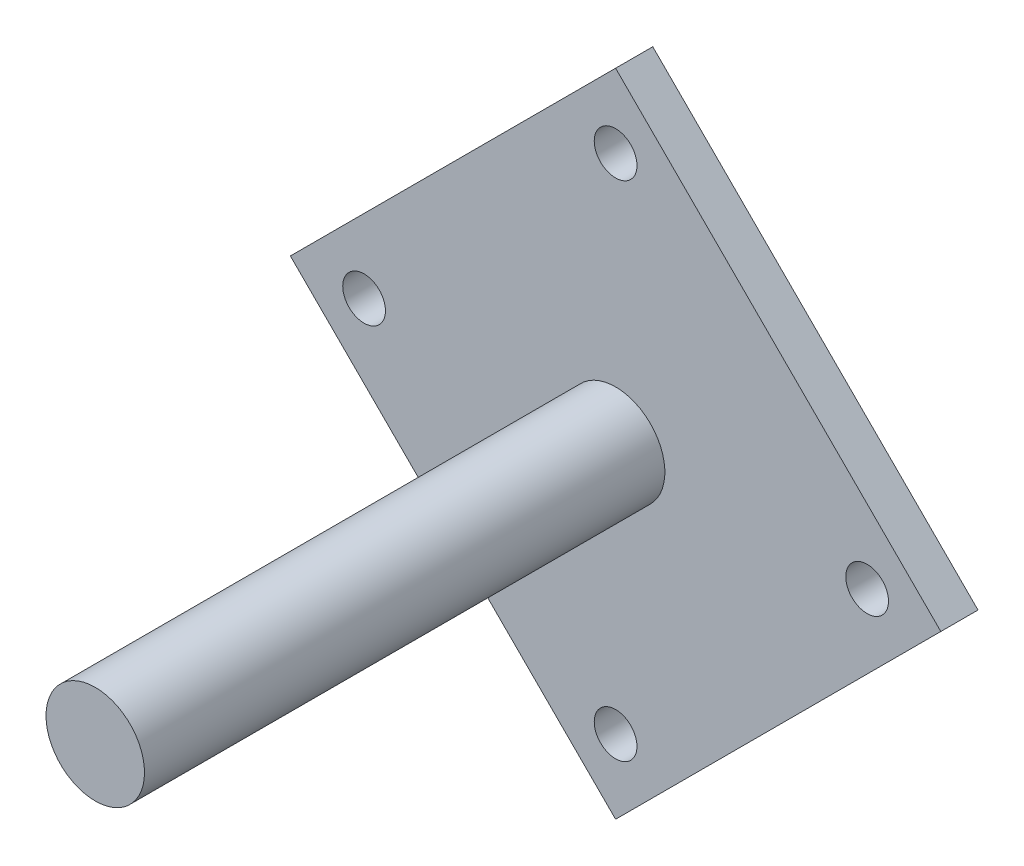
SolidWorks part; units mm, degrees
ref_plane "정면" through (0, 0, 0) normal (0, 0, 1) x (1, 0, 0)
ref_plane "윗면" through (0, 0, 0) normal (0, 1, 0) x (1, 0, 0)
ref_plane "우측면" through (0, 0, 0) normal (1, 0, 0) x (0, 0, -1)
sketch "스케치1" plane through (0, 0, 0) normal (0, 0, 1) x (1, 0, 0)
  circle A0 centre (0, 0) radius 2.65
  dimension "D1" = 5.3
extrude "보스-돌출1" add sketch "스케치1" along normal blind 30
sketch "스케치2" plane through (0, 0, 0) normal (0, 0, -1) x (-1, 0, 0)
  line L1 (17.5, -17.5) -> (-17.5, -17.5)
  line L2 (17.5, -17.5) -> (17.5, 17.5)
  line L3 (17.5, 17.5) -> (-17.5, 17.5)
  line L4 (-17.5, -17.5) -> (-17.5, 17.5)
  line L5 (17.5, -17.5) -> (-17.5, 17.5) construction
  line L6 (17.5, 17.5) -> (-17.5, -17.5) construction
  point P0 (0, 0)
  dimension "D1" = 35
  dimension "D2" = 35
extrude "보스-돌출2" add sketch "스케치2" against normal blind 2
sketch "스케치3" plane through (0, 0, 2) normal (0, 0, 1) x (1, 0, 0)
  line L0 (0, 0) -> (0, 3.071) construction
  circle A0 centre (6.5, 0) radius 1.15
  circle A1 centre (0, -6.5) radius 1.15
  circle A2 centre (-6.5, 0) radius 1.15
  circle A3 centre (0, 6.5) radius 1.15
  point P14 (0, 0)
  point P16 (0, 0)
  dimension "D2" = 2.3
  dimension "D1" = 6.5
  dimension "D3" = 4
ref_plane "평면1" through (0, 0, 4) normal (0, 0, 1) x (1, 0, 0)
sketch "스케치5" plane through (17.5, 0, 0) normal (1, 0, 0) x (0, 0, -1)
  line L0 (-23.7, 0) -> (-23.7, 6.152) construction
  line L3 (0, 17.5) -> (0, -17.5) construction
  circle A0 centre (-24.85, 0) radius 1.15
  dimension "D2" = 2.3
  dimension "D1" = 23.7
sketch "스케치7" plane through (0, 0, 0) normal (0, 0, -1) x (-1, 0, 0)
  circle A0 centre (0, 0) radius 10
  dimension "D1" = 20
sketch "스케치8" plane through (0, 0, 0) normal (0, 0, -1) x (-1, 0, 0)
  circle A0 centre (13.5337, 0) radius 1.15
  circle A1 centre (0, -13.5337) radius 1.15
  circle A2 centre (-13.5337, 0) radius 1.15
  circle A3 centre (0, 13.5337) radius 1.15
  point P11 (0, 0)
  dimension "D1" = 2.3
  dimension "D2" = 4
extrude "컷-돌출5" cut sketch "스케치8" against normal blind 5
sketch "스케치10" plane through (0, 0, 2) normal (0, 0, 1) x (1, 0, 0)
  line L0 (-17.5, 0) -> (0, 17.5)
  line L1 (-17.5, -17.5) -> (-17.5, 17.5) construction
  line L2 (-17.5, 17.5) -> (17.5, 17.5) construction
  line L3 (0, 17.5) -> (17.5, 0)
  line L4 (17.5, 17.5) -> (17.5, -17.5) construction
  line L5 (17.5, 0) -> (0, -17.5)
  line L6 (17.5, -17.5) -> (-17.5, -17.5) construction
  line L7 (0, -17.5) -> (-17.5, 0)
extrude "컷-돌출6" cut sketch "스케치10" against normal blind 5 flip side to cut
sketch "스케치11" plane through (0, 0, 30) normal (0, 0, 1) x (1, 0, 0)
  line L0 (0, 0) -> (0, 10.6826) construction
